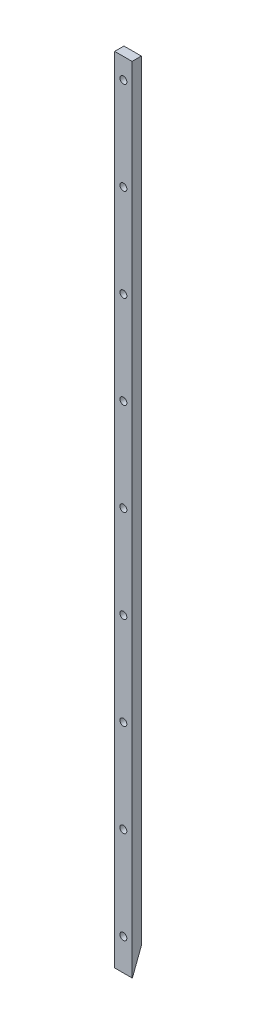
SolidWorks part; units mm, degrees
material "Brass"
ref_plane "Front Plane" through (0, 0, 0) normal (0, 0, 1) x (1, 0, 0)
ref_plane "Top Plane" through (0, 0, 0) normal (0, 1, 0) x (1, 0, 0)
ref_plane "Right Plane" through (0, 0, 0) normal (1, 0, 0) x (0, 0, -1)
sketch "Sketch1" plane through (0, 0, 0) normal (0, 0, 1) x (1, 0, 0)
  line L1 (-7.5, -342.5) -> (7.5, -342.5)
  line L2 (-7.5, -342.5) -> (-7.5, 342.5)
  line L3 (-7.5, 342.5) -> (7.5, 342.5)
  line L4 (7.5, -342.5) -> (7.5, 342.5)
  line L5 (-7.5, -342.5) -> (7.5, 342.5) construction
  line L6 (-7.5, 342.5) -> (7.5, -342.5) construction
  point P0 (0, 0)
  dimension "D1" = 685
  dimension "D2" = 15
extrude "Boss-Extrude1" add sketch "Sketch1" along normal mid plane 8
sketch "Sketch2" plane through (0, 0, 4) normal (0, 0, 1) x (1, 0, 0)
  line L0 (7.5, 342.5) -> (-7.5, 342.5) construction
  line L1 (-7.5, 342.5) -> (-7.5, -342.5) construction
  circle A0 centre (0, 324.8623) radius 3
  dimension "D1" = 6
  dimension "D3" = 7.5
  dimension "D2" = 17.6377
extrude "Cut-Extrude1" cut sketch "Sketch2" against normal blind 8
chamfer "Chamfer1" distance 20 angle 21 1 edges at (0, -342.5, -4)
pattern_linear "LPattern1" count 9 spacing 80 along (0, -1, 0) of "Cut-Extrude1"
chamfer "Chamfer2" distance 3 angle 45 9 edges at (3, 324.8623, -4) (3, 244.8623, -4) (3, 164.8623, -4) (3, 84.8623, -4) (3, 4.8623, -4) (3, -75.1377, -4) (3, -155.1377, -4) (3, -235.1377, -4) (3, -315.1377, -4)
